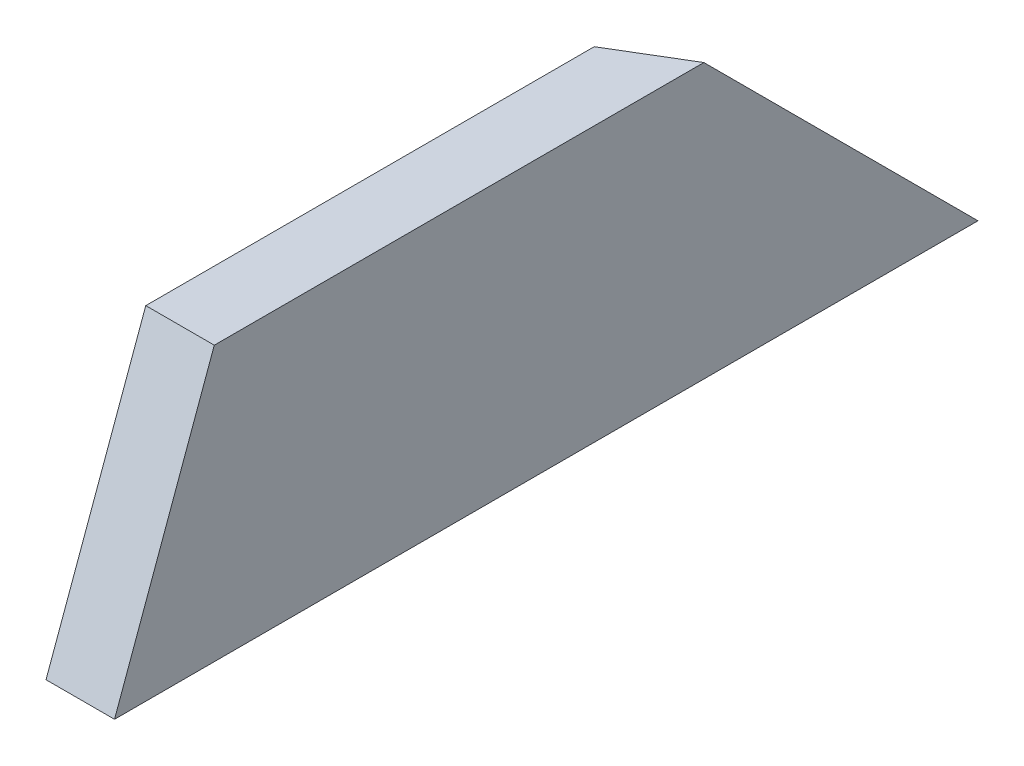
SolidWorks part; units mm, degrees
material "PE High Density"
ref_plane "Front Plane" through (0, 0, 0) normal (0, 0, 1) x (1, 0, 0)
ref_plane "Top Plane" through (0, 0, 0) normal (0, 1, 0) x (1, 0, 0)
ref_plane "Right Plane" through (0, 0, 0) normal (1, 0, 0) x (0, 0, -1)
sketch "Sketch1" plane through (0, 0, 0) normal (1, 0, 0) x (0, 0, -1)
  line L0 (-80.01, 0) -> (80.01, 0)
  line L1 (80.01, 0) -> (29.21, 50.8)
  line L2 (29.21, 50.8) -> (-61.5203, 50.8)
  line L3 (-61.5203, 50.8) -> (-80.01, 0)
  point P4 (0, 0)
  dimension "D1" = 45
  dimension "D2" = 160.02
  dimension "D3" = 50.8
  dimension "D4" = 70
extrude "Boss-Extrude1" add sketch "Sketch1" along normal blind 12.7
sketch "Sketch6" plane through (0, 0, 0) normal (0, -1, 0) x (1, 0, 0)
  line L0 (0, -80.01) -> (12.7, -80.01)
  line L4 (12.7, -80.01) -> (0, -72.39)
  line L5 (0, 80.01) -> (0, -80.01) construction
  line L6 (0, -72.39) -> (0, -80.01)
  dimension "D1" = 152.4
extrude "Cut-Extrude3" cut sketch "Sketch6" along direction (0, 0.7071, 0.7071) on the side against the normal up to surface (71.842 mm away)
